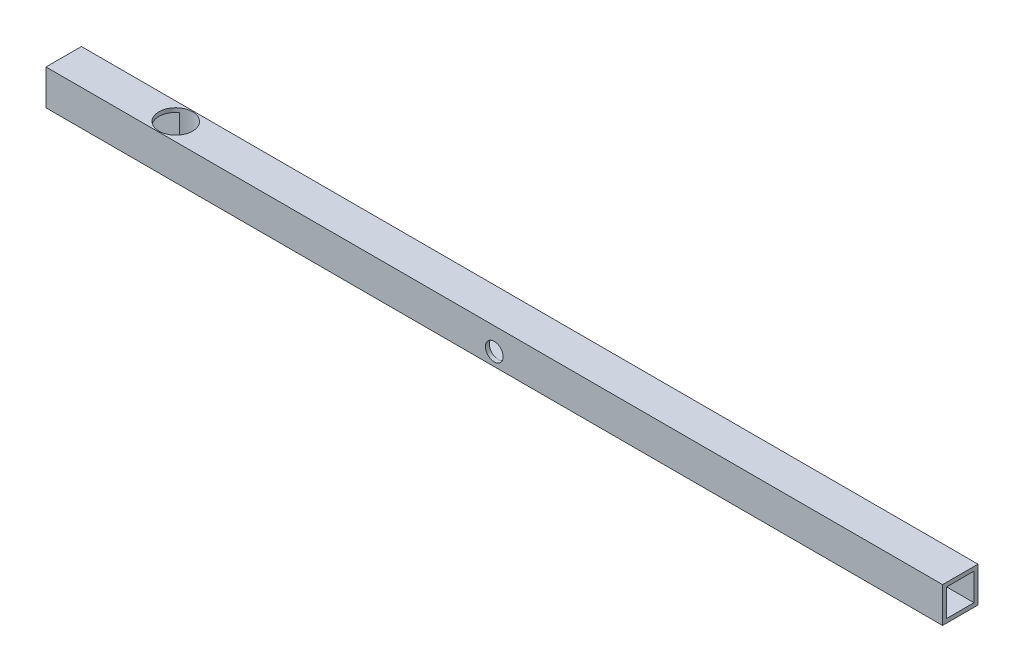
SolidWorks part; units mm, degrees
ref_plane "Front Plane" through (0, 0, 0) normal (0, 0, 1) x (1, 0, 0)
ref_plane "Top Plane" through (0, 0, 0) normal (0, 1, 0) x (1, 0, 0)
ref_plane "Right Plane" through (0, 0, 0) normal (1, 0, 0) x (0, 0, -1)
sketch "Sketch1" plane through (0, 0, 0) normal (1, 0, 0) x (0, 0, -1)
  line L0 (0.36, 2.8) -> (2.8, 2.8)
  line L1 (0, 0) -> (3.16, 0)
  line L2 (0, 0) -> (0, 3.16)
  line L3 (0, 3.16) -> (3.16, 3.16)
  line L4 (3.16, 0) -> (3.16, 3.16)
  line L5 (2.8, 0.36) -> (2.8, 2.8)
  line L6 (0.36, 0.36) -> (2.8, 0.36)
  line L7 (0.36, 0.36) -> (0.36, 2.8)
  dimension "D1" = 3.16
  dimension "D2" = 0.36
extrude "Boss-Extrude1" add sketch "Sketch1" along normal blind 80
sketch "Sketch2" plane through (0, 0, 0) normal (0, 0, 1) x (1, 0, 0)
  line L1 (0, 1.16) -> (40, 1.16) construction
  line L2 (0, 3.16) -> (0, 0) construction
  circle A0 centre (40, 1.16) radius 0.7937
  dimension "D1" = 1.5875
  dimension "D2" = 40
  dimension "D3" = 2
extrude "Cut-Extrude1" cut sketch "Sketch2" against normal through all
sketch "Sketch3" plane through (0, 3.16, 0) normal (0, 1, 0) x (1, 0, 0)
  line L0 (0, 1.58) -> (10, 1.58) construction
  line L1 (0, 3.16) -> (0, 0) construction
  circle A0 centre (10, 1.58) radius 1.5
  dimension "D1" = 3
  dimension "D2" = 10
extrude "Cut-Extrude2" cut sketch "Sketch3" against normal through all
